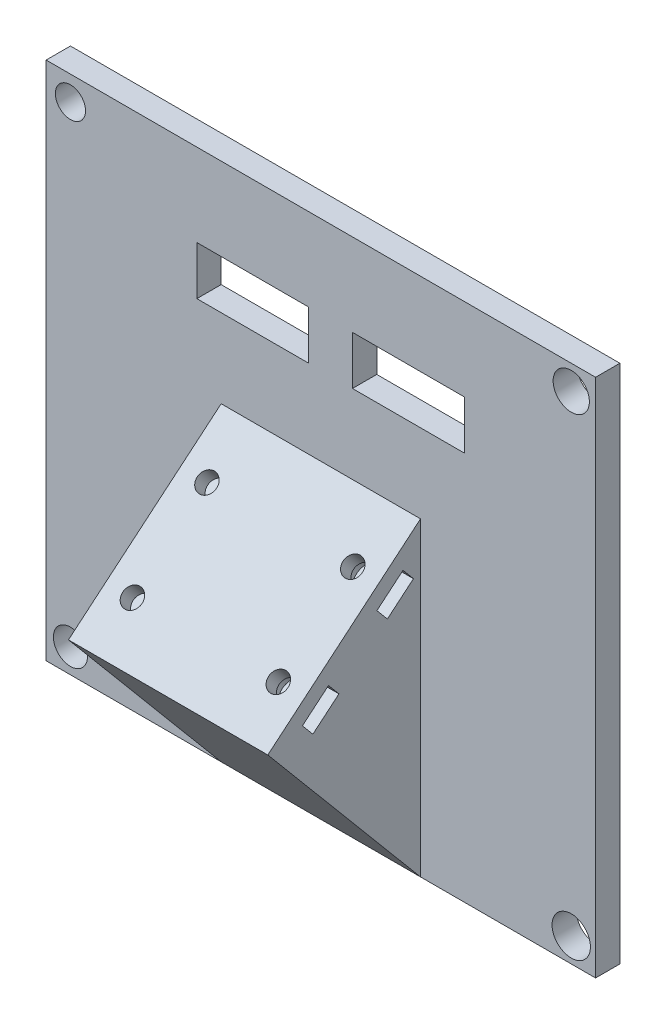
SolidWorks part; units mm, degrees
ref_plane "Front Plane" through (0, 0, 0) normal (0, 0, 1) x (1, 0, 0)
ref_plane "Top Plane" through (0, 0, 0) normal (0, 1, 0) x (1, 0, 0)
ref_plane "Right Plane" through (0, 0, 0) normal (1, 0, 0) x (0, 0, -1)
sketch "Sketch1" plane through (0, 0, 0) normal (0, 0, 1) x (1, 0, 0)
  line L1 (-56.5, -53.5) -> (56.5, -53.5)
  line L2 (-56.5, -53.5) -> (-56.5, 53.5)
  line L3 (-56.5, 53.5) -> (56.5, 53.5)
  line L4 (56.5, -53.5) -> (56.5, 53.5)
  line L5 (-56.5, -53.5) -> (56.5, 53.5) construction
  line L6 (-56.5, 53.5) -> (56.5, -53.5) construction
  point P0 (0, 0)
  dimension "D1" = 113
  dimension "D2" = 107
extrude "Boss-Extrude1" add sketch "Sketch1" along normal blind 20
sketch "Sketch2" plane through (0, 0, 0) normal (0, 0, -1) x (-1, 0, 0)
  line L5 (-46.5, 43.5) -> (46.5, 43.5)
  line L6 (-46.5, 43.5) -> (-46.5, -43.5)
  line L9 (-46.5, -43.5) -> (46.5, -43.5)
  line L10 (46.5, 43.5) -> (46.5, -43.5)
  line L11 (-46.5, 43.5) -> (46.5, -43.5) construction
  line L12 (-46.5, -43.5) -> (46.5, 43.5) construction
  point P0 (0, 0)
  dimension "D1" = 93
  dimension "D2" = 87
extrude "Cut-Extrude1" cut sketch "Sketch2" against normal blind 15
sketch "Sketch7" plane through (0, 0, 15) normal (0, 0, -1) x (-1, 0, 0)
  line L0 (46.5, 43.5) -> (-46.5, 43.5) construction
  line L5 (46.5, -43.5) -> (46.5, 43.5) construction
  line L14 (-18, 31.5) -> (14, 31.5) construction
  line L15 (-29.5, 26.5) -> (-6.5, 26.5)
  line L16 (-29.5, 26.5) -> (-29.5, 36.5)
  line L17 (-29.5, 36.5) -> (-6.5, 36.5)
  line L18 (-6.5, 26.5) -> (-6.5, 36.5)
  line L19 (-29.5, 26.5) -> (-6.5, 36.5) construction
  line L20 (-29.5, 36.5) -> (-6.5, 26.5) construction
  line L21 (2.5, 26.5) -> (25.5, 26.5)
  line L22 (2.5, 26.5) -> (2.5, 36.5)
  line L23 (2.5, 36.5) -> (25.5, 36.5)
  line L24 (25.5, 26.5) -> (25.5, 36.5)
  line L25 (2.5, 26.5) -> (25.5, 36.5) construction
  line L26 (2.5, 36.5) -> (25.5, 26.5) construction
  point P14 (-18, 31.5)
  point P19 (14, 31.5)
  dimension "D1" = 7
  dimension "D2" = 9
  dimension "D3" = 21
  dimension "D6" = 23
  dimension "D7" = 23
  dimension "D8" = 10
  dimension "D9" = 10
ref_plane "Plane2" through (0, 0, 0) normal (-1, 0, 0) x (0, 0, 1)
sketch "Sketch9" plane through (0, 0, 0) normal (-1, 0, 0) x (0, 0, 1)
  line L0 (20, -53.5) -> (51.4078, -16.0696)
  line L1 (51.4078, -16.0696) -> (20, 10.2847)
  line L2 (20, 53.5) -> (20, -53.5) construction
  line L3 (20, 10.2847) -> (20, -53.5)
  dimension "D1" = 41
  dimension "D2" = 40
extrude "Boss-Extrude4" add sketch "Sketch9" along normal mid plane 41
extrude "Cut-Extrude2" cut sketch "Sketch7" against normal blind 41
sketch "Sketch10" plane through (0, 0, 0) normal (0, 0, -1) x (-1, 0, 0)
  line L0 (-56.5, 53.5) -> (56.5, 53.5) construction
  line L1 (-56.5, -53.5) -> (-56.5, 53.5) construction
  line L2 (56.5, 53.5) -> (56.5, -53.5) construction
  line L3 (56.5, -53.5) -> (-56.5, -53.5) construction
  circle A0 centre (-51.5, 48.5) radius 3.7276
  circle A1 centre (51.5, 48.5) radius 3.0999
  circle A2 centre (51.5, -48.5) radius 3.5031
  circle A3 centre (-51.5, -48.5) radius 3.9462
  dimension "D1" = 5
  dimension "D2" = 5
  dimension "D3" = 5
  dimension "D4" = 5
  dimension "D5" = 5
  dimension "D6" = 5
  dimension "D7" = 5
  dimension "D8" = 5
extrude "Cut-Extrude3" cut sketch "Sketch10" against normal through all
sketch "Sketch11" plane through (0, 0, 10) normal (0, 0, -1) x (-1, 0, 0)
  line L0 (-51.5, -53) -> (-56.5, -53)
  line L1 (-56.5, -53.5) -> (-56.5, 53.5) construction
  line L2 (-56.5, -53) -> (-56.5, -44)
  line L3 (-56.5, -44) -> (-51.5, -44)
  line L4 (0, -53.5) -> (0, 53.5) construction
  line L5 (56.5, -53.5) -> (-56.5, -53.5) construction
  line L6 (-56.5, 53.5) -> (56.5, 53.5) construction
  line L7 (-56.5, 0) -> (56.5, 0) construction
  line L8 (56.5, 53.5) -> (56.5, -53.5) construction
  line L9 (-56.5, 44) -> (-51.5, 44)
  line L10 (-56.5, 53) -> (-56.5, 44)
  line L11 (-51.5, 53) -> (-56.5, 53)
  line L12 (51.5, 53) -> (56.5, 53)
  line L13 (56.5, 53) -> (56.5, 44)
  line L14 (56.5, 44) -> (51.5, 44)
  line L15 (56.5, -44) -> (51.5, -44)
  line L16 (56.5, -53) -> (56.5, -44)
  line L17 (51.5, -53) -> (56.5, -53)
  arc A0 (-51.5, -53) -> (-51.5, -44) centre (-51.5, -48.5) ccw
  arc A1 (-51.5, 53) -> (-51.5, 44) centre (-51.5, 48.5) cw
  arc A2 (51.5, 53) -> (51.5, 44) centre (51.5, 48.5) ccw
  arc A3 (51.5, -53) -> (51.5, -44) centre (51.5, -48.5) cw
  dimension "D1" = 4.5
extrude "Cut-Extrude4" [suppressed] cut sketch "Sketch11" along normal blind 3
sketch "Sketch12" plane through (0, 15.8834, 13.3277) normal (0, 0.766, 0.6428) x (1, 0, 0)
  line L0 (-15, -19.71) -> (15, -19.71) construction
  line L1 (15, -19.71) -> (15, -39.71) construction
  line L2 (-15, -19.71) -> (-14.9999, -39.71) construction
  line L3 (-14.9999, -39.71) -> (15, -39.71) construction
  line L4 (0, -8.71) -> (0, -49.71) construction
  line L5 (-20.5, -8.71) -> (20.5, -8.71) construction
  line L6 (-20.5, -49.71) -> (20.5, -49.71) construction
  circle A0 centre (-15, -19.71) radius 2
  circle A1 centre (15, -19.71) radius 2
  circle A2 centre (-14.9999, -39.71) radius 2
  circle A3 centre (15, -39.71) radius 2
  point P14 (0, -19.71)
  dimension "D1" = 4
  dimension "D2" = 30
  dimension "D3" = 10
  dimension "D4" = 20
extrude "Cut-Extrude5" cut sketch "Sketch12" against normal blind 10
ref_plane "Plane3" through (0, 12.0532, 10.1138) normal (0, 0.766, 0.6428) x (1, 0, 0)
sketch "Sketch14" plane through (0, 12.0532, 10.1138) normal (0, 0.766, 0.6428) x (1, 0, 0)
  line L1 (-20.5, -16.21) -> (-20.5, -23.21)
  line L4 (-20.5, -36.21) -> (-20.5, -43.21)
  line L7 (20.5, -43.21) -> (20.5, -36.21)
  line L10 (20.5, -23.21) -> (20.5, -16.21)
  line L12 (-20.5, -49.71) -> (-20.5, -8.71) construction
  line L13 (20.5, -49.71) -> (20.5, -8.71) construction
  line L14 (-15, -16.21) -> (-20.5, -16.21)
  line L15 (-15, -23.21) -> (-20.5, -23.21)
  line L16 (-14.9999, -36.21) -> (-20.5, -36.21)
  line L17 (-14.9999, -43.21) -> (-20.5, -43.21)
  line L18 (15, -16.21) -> (20.5, -16.21)
  line L19 (15, -23.21) -> (20.5, -23.21)
  line L20 (15, -36.21) -> (20.5, -36.21)
  line L21 (15, -43.21) -> (20.5, -43.21)
  arc A8 (-15, -23.21) -> (-15, -16.21) centre (-15, -19.71) ccw
  arc A9 (-14.9999, -43.21) -> (-14.9999, -36.21) centre (-14.9999, -39.71) ccw
  arc A10 (15, -36.21) -> (15, -43.21) centre (15, -39.71) ccw
  arc A11 (15, -16.21) -> (15, -23.21) centre (15, -19.71) ccw
  dimension "D1" = 7
extrude "Cut-Extrude6" cut sketch "Sketch14" against normal mid plane 3.35
sketch "Sketch15" plane through (0, 0, 15) normal (0, 0, -1) x (-1, 0, 0)
  line L1 (-59.1814, -55.5706) -> (59.1814, -55.5706)
  line L2 (-59.1814, -55.5706) -> (-59.1814, 55.5706)
  line L3 (-59.1814, 55.5706) -> (59.1814, 55.5706)
  line L4 (59.1814, -55.5706) -> (59.1814, 55.5706)
  line L5 (-59.1814, -55.5706) -> (59.1814, 55.5706) construction
  line L6 (-59.1814, 55.5706) -> (59.1814, -55.5706) construction
  point P0 (0, 0)
extrude "Cut-Extrude7" cut sketch "Sketch15" along normal through all
